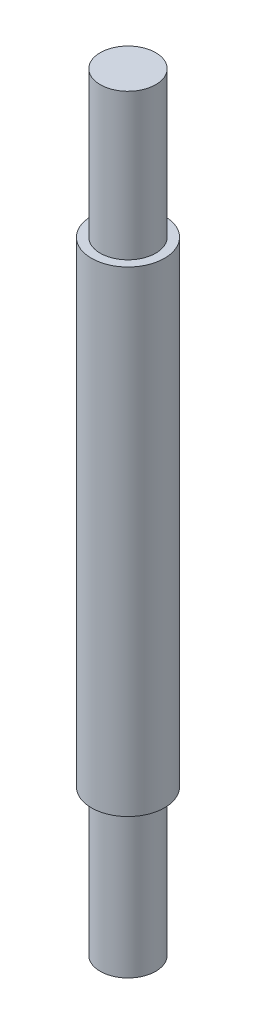
SolidWorks part; units mm, degrees
ref_plane "Front Plane" through (0, 0, 0) normal (0, 0, 1) x (1, 0, 0)
ref_plane "Top Plane" through (0, 0, 0) normal (0, 1, 0) x (1, 0, 0)
ref_plane "Right Plane" through (0, 0, 0) normal (1, 0, 0) x (0, 0, -1)
sketch "Sketch2" plane through (0, 0, 0) normal (0, 1, 0) x (1, 0, 0)
  circle A0 centre (0, 0) radius 3.175
  dimension "D1" = 6.35
extrude "Boss-Extrude1" add sketch "Sketch2" along normal mid plane 41.402
sketch "Sketch3" plane through (0, 20.701, 0) normal (0, 1, 0) x (1, 0, 0)
  circle A0 centre (0, 0) radius 2.413
  dimension "D1" = 4.826
extrude "Boss-Extrude2" add sketch "Sketch3" along normal mid plane 25.4
mirror "Mirror1" about plane through (0, 0, 0) normal (0, 1, 0) of "Boss-Extrude2"
